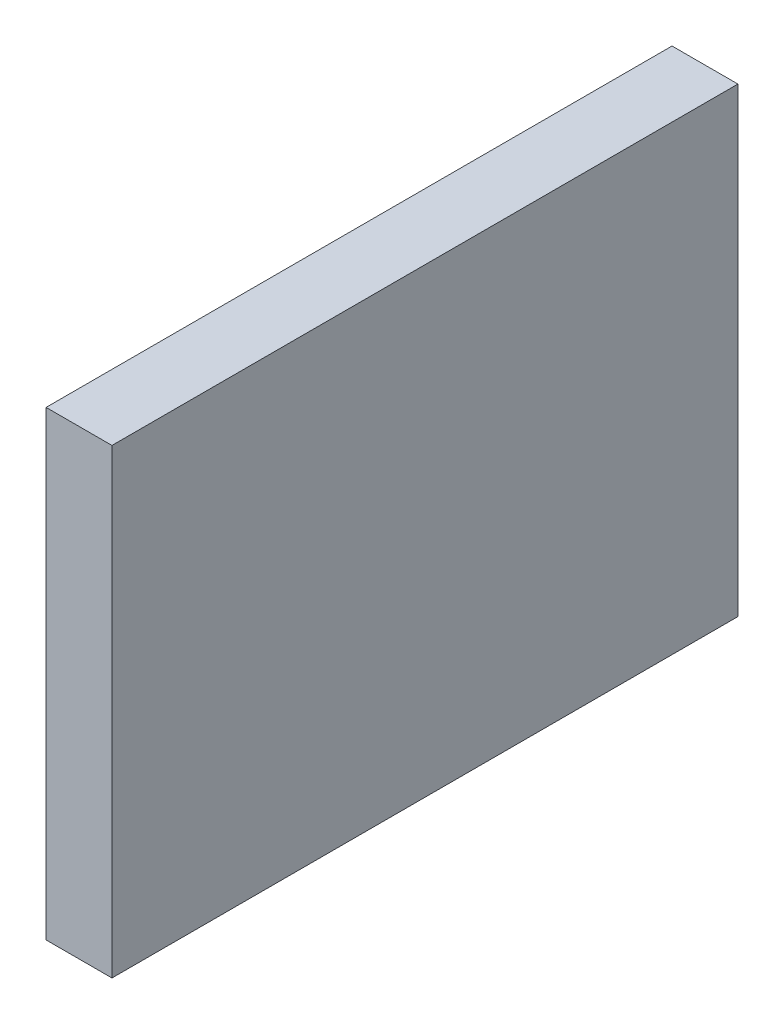
SolidWorks part; units mm, degrees
ref_plane "Front Plane" through (0, 0, 0) normal (0, 0, 1) x (1, 0, 0)
ref_plane "Top Plane" through (0, 0, 0) normal (0, 1, 0) x (1, 0, 0)
ref_plane "Right Plane" through (0, 0, 0) normal (1, 0, 0) x (0, 0, -1)
sketch "Sketch1" plane through (0, 0, 0) normal (0, 0, 1) x (1, 0, 0)
  line L1 (-1, 7) -> (1, 7)
  line L2 (-1, 7) -> (-1, -7)
  line L3 (-1, -7) -> (1, -7)
  line L4 (1, 7) -> (1, -7)
  line L5 (-1, 7) -> (1, -7) construction
  line L6 (-1, -7) -> (1, 7) construction
  point P0 (0, 0)
  dimension "D1" = 14
  dimension "D2" = 2
extrude "Boss-Extrude1" add sketch "Sketch1" along normal blind 23
sketch "Sketch2" plane through (-1, 0, 0) normal (-1, 0, 0) x (0, 0, 1)
  line L0 (2, 7) -> (2, -7)
  line L1 (23, 7) -> (0, 7) construction
  line L2 (23, -7) -> (0, -7) construction
  line L3 (2, -7) -> (0, -7)
  line L4 (0, -7) -> (0, 7)
  line L5 (0, 7) -> (2, 7)
  dimension "D1" = 2
extrude "Cut-Extrude1" cut sketch "Sketch2" against normal blind 10
sketch "Sketch3" plane through (-1, 0, 0) normal (-1, 0, 0) x (0, 0, 1)
  line L0 (4, 7) -> (4, -7)
  line L1 (23, 7) -> (2, 7) construction
  line L2 (23, -7) -> (2, -7) construction
  line L3 (4, -7) -> (2, -7)
  line L4 (2, -7) -> (2, 7)
  line L5 (2, 7) -> (3.4402, 7)
  line L6 (3.4402, 7) -> (4, 7)
  dimension "D1" = 2
extrude "Cut-Extrude2" cut sketch "Sketch3" against normal blind 10
